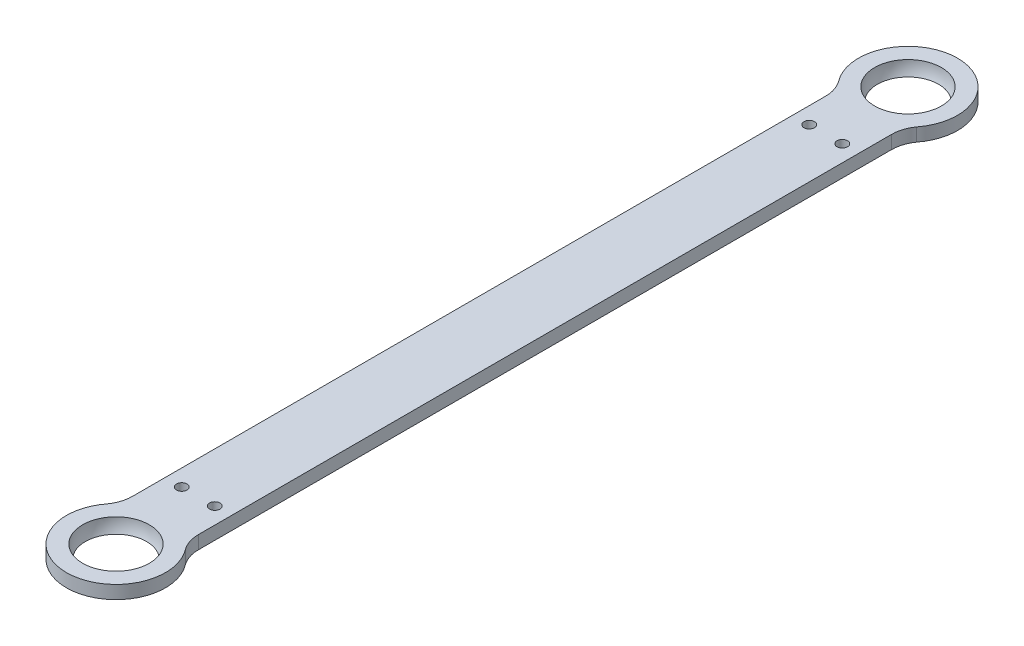
SolidWorks part; units mm, degrees
ref_plane "Front Plane" through (0, 0, 0) normal (0, 0, 1) x (1, 0, 0)
ref_plane "Top Plane" through (0, 0, 0) normal (0, 1, 0) x (1, 0, 0)
ref_plane "Right Plane" through (0, 0, 0) normal (1, 0, 0) x (0, 0, -1)
sketch "Sketch1" plane through (0, 0, 0) normal (0, 1, 0) x (1, 0, 0)
  line L0 (-10, -15) -> (-10, -34.8037)
  line L3 (-10, -34.8037) -> (10, -34.8037)
  line L4 (10, -15) -> (10, -34.8037)
  arc A0 (11.846, -9.2018) -> (-11.846, -9.2018) centre (0, 0) ccw
  arc A1 (10, -15) -> (11.846, -9.2018) centre (20.0291, -15) cw
  arc A2 (-10, -15) -> (-11.846, -9.2018) centre (-20.0291, -15) ccw
  dimension "D1" = 30
  dimension "D2" = 20
extrude "Boss-Extrude1" add sketch "Sketch1" along normal blind 4
sketch "Sketch2" plane through (0, 4, 0) normal (0, 1, 0) x (1, 0, 0)
  line L0 (0, 10.1) -> (0, -10.1)
  arc A0 (0, -10.1) -> (0, 10.1) centre (0, 0) ccw
  dimension "D1" = 20.2
revolve "Cut-Revolve1" cut sketch "Sketch2" angle 360 about L0
sketch "Sketch3" plane through (0, 4, 0) normal (0, 1, 0) x (1, 0, 0)
  line L0 (0, -24.9018) -> (0, -39.9743) construction
  line L1 (10, -24.9018) -> (10, -39.9743)
  line L2 (-10, -24.9018) -> (-10, -39.9743)
  arc A0 (10, -24.9018) -> (-10, -24.9018) centre (0, -24.9018) ccw
  arc A1 (-10, -39.9743) -> (10, -39.9743) centre (0, -39.9743) ccw
  point P4 (0, -32.4381)
  dimension "D1" = 10
extrude "Cut-Extrude1" cut sketch "Sketch3" against normal blind 1
sketch "Sketch4" plane through (0, 3, 0) normal (0, 1, 0) x (1, 0, 0)
  line L0 (10, -34.8037) -> (10, -24.9018) construction
  line L1 (0, -14.9018) -> (13.6723, -14.9018) construction
  line L2 (0, -14.9018) -> (0, -28.3768) construction
  circle A0 centre (5, -24.9018) radius 1.6
  arc A3 (10, -24.9018) -> (-10, -24.9018) centre (0, -24.9018) ccw construction
  circle A4 centre (-5, -24.9018) radius 1.6
  dimension "D1" = 3.2
  dimension "D2" = 5
  dimension "D3" = 10
extrude "Cut-Extrude2" cut sketch "Sketch4" against normal blind 10
sketch "Sketch6" plane through (0, 3, 0) normal (0, 1, 0) x (1, 0, 0)
  line L0 (10, -34.8037) -> (10, -24.9018)
  line L1 (-10, -34.8037) -> (10, -34.8037)
  line L2 (-10, -24.9018) -> (-10, -34.8037) construction
  line L3 (-10, -24.9018) -> (-10, -34.8037)
  line L6 (-10, -34.8037) -> (10, -34.8037)
  line L7 (10, -34.8037) -> (10, -24.9018)
  line L8 (-10, -24.9018) -> (-10, -34.8037)
  line L10 (10, -34.8037) -> (10, -24.9018)
  line L11 (-10, -24.9018) -> (-10, -34.8037)
  arc A0 (10, -24.9018) -> (-10, -24.9018) centre (0, -24.9018) ccw construction
  arc A1 (-10, -24.9018) -> (10, -24.9018) centre (0, -24.9018) cw
  arc A3 (10, -24.9018) -> (-10, -24.9018) centre (0, -24.9018) ccw
  arc A4 (10, -24.9018) -> (-10, -24.9018) centre (0, -24.9018) ccw
  circle M5 centre (5, -24.9018) radius 1.6
  circle M6 centre (-5, -24.9018) radius 1.6
  line M7 (-10, -34.8037) -> (10, -34.8037)
  line M8 (10, -34.8037) -> (10, -24.9018)
  arc M9 (10, -24.9018) -> (-10, -24.9018) centre (0, -24.9018) ccw
  line M10 (-10, -24.9018) -> (-10, -34.8037)
  dimension "D1" = 0
extrude "Boss-Extrude2" add sketch "Sketch6" along normal up to surface (1 mm away) contours M10 M7 M8 M9 M6 M5 up to face at (0, 4, -10.1)
sketch "Sketch7" plane through (0, 0, 34.8037) normal (0, 0, 1) x (1, 0, 0)
  line L1 (-10, 0) -> (10, 0)
  line L2 (-10, 0) -> (-10, 4)
  line L3 (-10, 4) -> (10, 4)
  line L4 (10, 0) -> (10, 4)
extrude "Boss-Extrude3" add sketch "Sketch7" along normal blind 85.1
mirror "Mirror3" about plane through (0, 0, 119.9037) normal (0, 0, -1) of bodies 106
